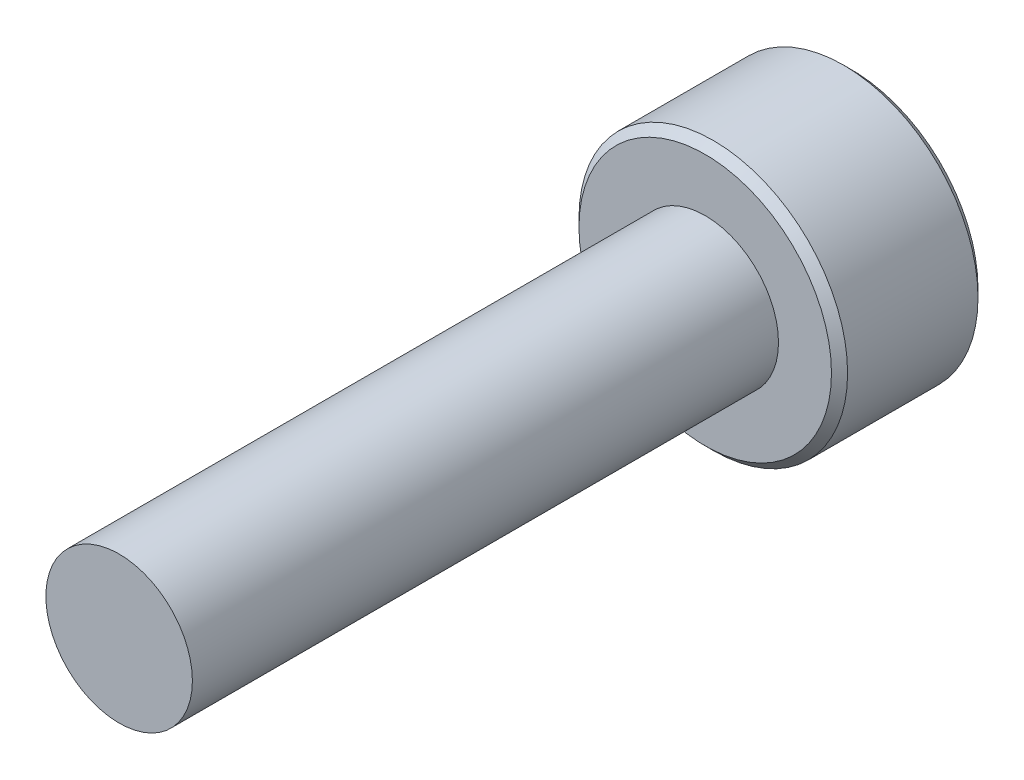
SolidWorks part; units mm, degrees
ref_plane "Front Plane" through (0, 0, 0) normal (0, 0, 1) x (1, 0, 0)
ref_plane "Top Plane" through (0, 0, 0) normal (0, 1, 0) x (1, 0, 0)
ref_plane "Right Plane" through (0, 0, 0) normal (1, 0, 0) x (0, 0, -1)
sketch "Sketch1" plane through (0, 0, 0) normal (0, 0, 1) x (1, 0, 0)
  circle A0 centre (0, 0) radius 1.5
  dimension "OD" = 3
extrude "Extrude1" add sketch "Sketch1" against normal blind 12
sketch "Sketch2" plane through (0, 0, 0) normal (0, 0, 1) x (1, 0, 0)
  circle A0 centre (0, 0) radius 1.5 construction
  circle A1 centre (0, 0) radius 1.5
curve "Helix/Spiral1" pitch 0.5 height 12.5 turns 25 parameters "pitch"=0.5
sketch "Sketch3" plane through (0, 0, 0) normal (1, 0, 0) x (0, 0, -1)
  line L0 (-0.4375, 1.5) -> (-0.25, 1.1752)
  line L1 (-0.25, 1.1752) -> (-0.1875, 1.1752)
  line L2 (-0.1875, 1.1752) -> (0, 1.5)
  line L3 (-0.4375, 1.5) -> (0, 1.5)
  line L4 (-0.2188, 1.5) -> (-0.2188, 1.1752) construction
  line L5 (-0.3438, 1.3376) -> (-0.0938, 1.3376) construction
  line L6 (0, 1.5) -> (0, -1.5) construction
  line L7 (0, -1.5) -> (12, -1.5) construction
  point P11 (2.25, -1.5)
  dimension "D1" = 0.0625
  dimension "D2" = 0.25
  dimension "D3" = 60
  dimension "D4" = 2.25
sketch "Sketch4" plane through (0, 0, 0) normal (1, 0, 0) x (0, 0, -1)
  line L0 (0.4053, 1.5) -> (0, 0.9212)
  line L1 (0, 0.9212) -> (0, 1.5)
  line L2 (0.4053, 1.5) -> (0, 1.5)
  line L3 (-0.4375, 1.5) -> (0, 1.5) construction
  line L4 (0, 0) -> (7.0209, 0) construction
  dimension "D1" = 55
  dimension "D2" = 0.254
sketch "Sketch6" plane through (0, 0, -12) normal (0, 0, -1) x (-1, 0, 0)
  circle A0 centre (0, 0) radius 2.75
  dimension "head dia" = 5.5
extrude "Extrude2" add sketch "Sketch6" along normal blind 3
sketch "Sketch7" plane through (0, 0, -15) normal (0, 0, -1) x (-1, 0, 0)
  line L1 (0, 1.4434) -> (-1.25, 0.7217)
  line L2 (-1.25, 0.7217) -> (-1.25, -0.7217)
  line L3 (-1.25, -0.7217) -> (0, -1.4434)
  line L4 (0, -1.4434) -> (1.25, -0.7217)
  line L5 (1.25, -0.7217) -> (1.25, 0.7217)
  line L6 (1.25, 0.7217) -> (0, 1.4434)
  circle A0 centre (0, 0) radius 1.25 construction
  dimension "hex dia" = 2.5
extrude "Cut-Extrude1" cut sketch "Sketch7" against normal blind 1.875
sketch "Sketch8" plane through (0, 0, -15) normal (0, 0, -1) x (-1, 0, 0)
  circle A0 centre (0, 0) radius 1.4434
extrude "Cut-Extrude2" cut sketch "Sketch8" against normal through all draft 45
chamfer "Chamfer1" distance 0.165 angle 45 2 edges at (-2.75, 0, -15) (-2.75, 0, -12)
sketch "Sketch9" plane through (0, 0, 0) normal (1, 0, 0) x (0, 0, -1)
  line L0 (0, 1.5) -> (0, -1.5) construction
  line L1 (2.75, 1.5) -> (2.75, -1.5) construction
  dimension "D1" = 2.75
sketch "Sketch10" plane through (0, 0, 0) normal (1, 0, 0) x (0, 0, -1)
  line L0 (12, 1.5) -> (12, 0)
  line L1 (12, 1.5) -> (11.875, 1.5)
  line L2 (11.875, 1.5) -> (11.2537, 0)
  line L3 (12, 0) -> (11.2537, 0)
  line L4 (12, 2.585) -> (12, -2.585) construction
  dimension "D1" = 22.5
  dimension "D2" = 0.125
revolve "Revolve1" add sketch "Sketch10" angle 360 about L3
equation "\"D3@Helix/Spiral1\" = \"screw length@Extrude1\"+\"pitch@Helix/Spiral1\""
equation "\"D1@Sketch3\" = \"pitch@Helix/Spiral1\"*.125"
equation "\"D2@Sketch3\" = \"pitch@Helix/Spiral1\"*.5"
equation "\"D1@Cut-Extrude1\" = \"hex dia@Sketch7\"*.75"
equation "\"D1@Chamfer1\" = \"head dia@Sketch6\"*.03"
equation "\"D1@Sketch9\" = \"pitch@Helix/Spiral1\"*5.5"
equation "\"D2@Sketch10\" = \"pitch@Helix/Spiral1\"*.25"
equation "\"D4@Sketch3\" = \"pitch@Helix/Spiral1\"*4.50"
